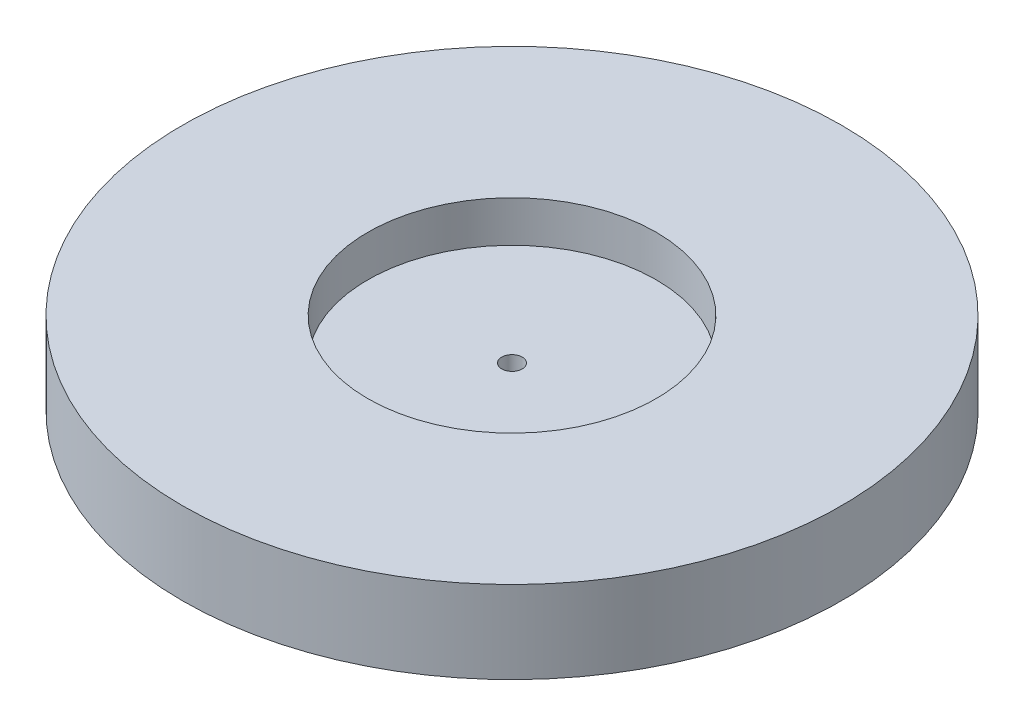
SolidWorks part; units mm, degrees
ref_plane "Front Plane" through (0, 0, 0) normal (0, 0, 1) x (1, 0, 0)
ref_plane "Top Plane" through (0, 0, 0) normal (0, 1, 0) x (1, 0, 0)
ref_plane "Right Plane" through (0, 0, 0) normal (1, 0, 0) x (0, 0, -1)
sketch "Sketch1" plane through (0, 0, 0) normal (0, 1, 0) x (1, 0, 0)
  circle A0 centre (0, 0) radius 101.6
  circle A1 centre (0, 0) radius 3.175
  dimension "D1" = 6.35
  dimension "D2" = 203.2
extrude "Boss-Extrude1" add sketch "Sketch1" along normal blind 25.4
sketch "Sketch3" plane through (0, 25.4, 0) normal (0, 1, 0) x (1, 0, 0)
  circle A0 centre (0, 0) radius 44.45
  dimension "D1" = 88.9
extrude "Cut-Extrude1" cut sketch "Sketch3" against normal blind 12.7
